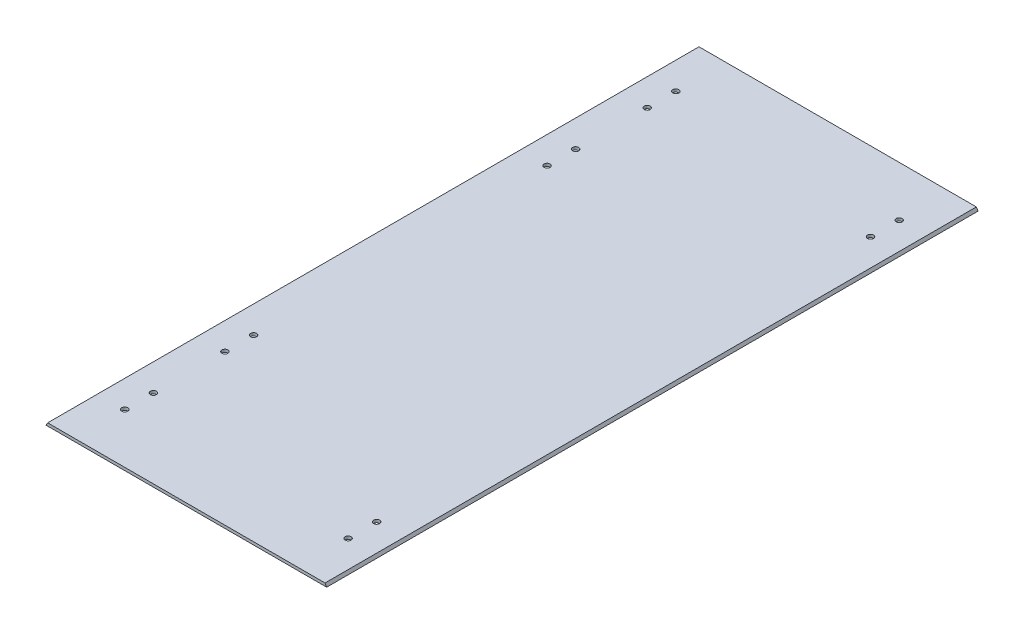
SolidWorks part; units mm, degrees
ref_plane "前视基准面" through (0, 0, 0) normal (0, 0, 1) x (1, 0, 0)
ref_plane "上视基准面" through (0, 0, 0) normal (0, 1, 0) x (1, 0, 0)
ref_plane "右视基准面" through (0, 0, 0) normal (1, 0, 0) x (0, 0, -1)
other "Configuration Table"
sketch "草图2" plane through (0, 0, 0) normal (0, 0, 1) x (1, 0, 0)
  line L0 (-98, -1) -> (-96.8453, 1)
  line L1 (-98, -1) -> (98.07, -1)
  line L3 (-96.8453, 1) -> (96.9153, 1)
  line L5 (-98, -1) -> (96.9217, 0.989) construction
  line L6 (-96.8525, 0.9876) -> (98.07, -1) construction
  line L7 (98.07, -1) -> (96.9153, 1)
  point P0 (0, 0)
  dimension "D1" = 60
  dimension "D2" = 196.07
  dimension "D3" = 60
  dimension "D4" = 2
  dimension "D5" = 1
extrude "凸台-拉伸1" add sketch "草图2" against normal blind 455
sketch "草图3" plane through (0, -1, 0) normal (0, -1, 0) x (-1, 0, 0)
  line L0 (98, 0) -> (-98.07, 0) construction
  line L1 (98, 455) -> (98, 0) construction
  line L2 (0, 0) -> (0, 458.5279) construction
  line L3 (98, 227.5) -> (-98.07, 227.5) construction
  line L4 (-98.07, 455) -> (-98.07, 0) construction
  circle A0 centre (78, 35) radius 2.1
  circle A1 centre (78, 55) radius 2.1
  circle A2 centre (-78, 55) radius 2.1
  circle A3 centre (-78, 35) radius 2.1
  circle A4 centre (-78, 420) radius 2.1
  circle A5 centre (-78, 400) radius 2.1
  circle A6 centre (78, 400) radius 2.1
  circle A7 centre (78, 420) radius 2.1
  circle A8 centre (78, 105) radius 2.1
  circle A9 centre (78, 125) radius 2.1
  circle A10 centre (78, 350) radius 2.1
  circle A11 centre (78, 330) radius 2.1
  dimension "D1" = 20
  dimension "D5" = 20
  dimension "D2" = 20
  dimension "D3" = 20
  dimension "D4" = 35
  dimension "D6" = 50
extrude "切除-拉伸1" cut sketch "草图3" against normal through all
sketch "草图5" plane through (0, -1, 0) normal (0, -1, 0) x (1, 0, 0)
  line L0 (0, 0) -> (0.035, -455) construction
  line L1 (-98, -455) -> (98.07, -455) construction
  line L2 (-98, -227.5) -> (98.07, -227.5) construction
  line L3 (-98, -455) -> (-98, 0) construction
  line L4 (98.07, -455) -> (98.07, 0) construction
